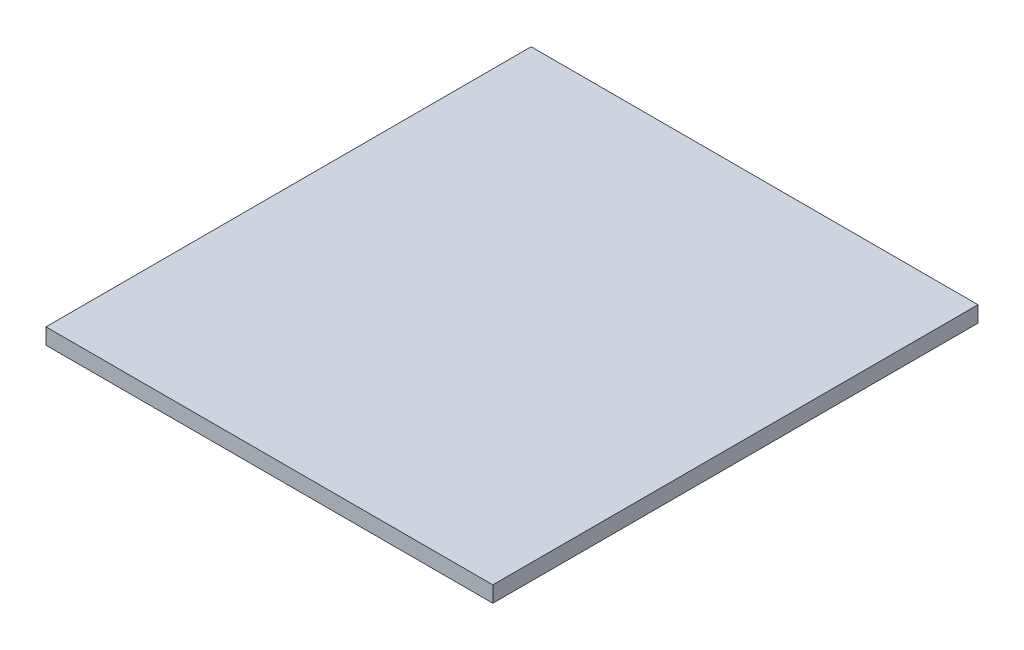
SolidWorks part; units mm, degrees
ref_plane "Front Plane" through (0, 0, 0) normal (0, 0, 1) x (1, 0, 0)
ref_plane "Top Plane" through (0, 0, 0) normal (0, 1, 0) x (1, 0, 0)
ref_plane "Right Plane" through (0, 0, 0) normal (1, 0, 0) x (0, 0, -1)
sketch "Sketch1" plane through (0, 0, 0) normal (0, 1, 0) x (1, 0, 0)
  line L1 (280, -304) -> (-280, -304)
  line L2 (280, -304) -> (280, 304)
  line L3 (280, 304) -> (-280, 304)
  line L4 (-280, -304) -> (-280, 304)
  line L5 (280, -304) -> (-280, 304) construction
  line L6 (280, 304) -> (-280, -304) construction
  point P0 (0, 0)
  dimension "D1" = 608
  dimension "D2" = 560
extrude "Boss-Extrude1" add sketch "Sketch1" along normal blind 20
